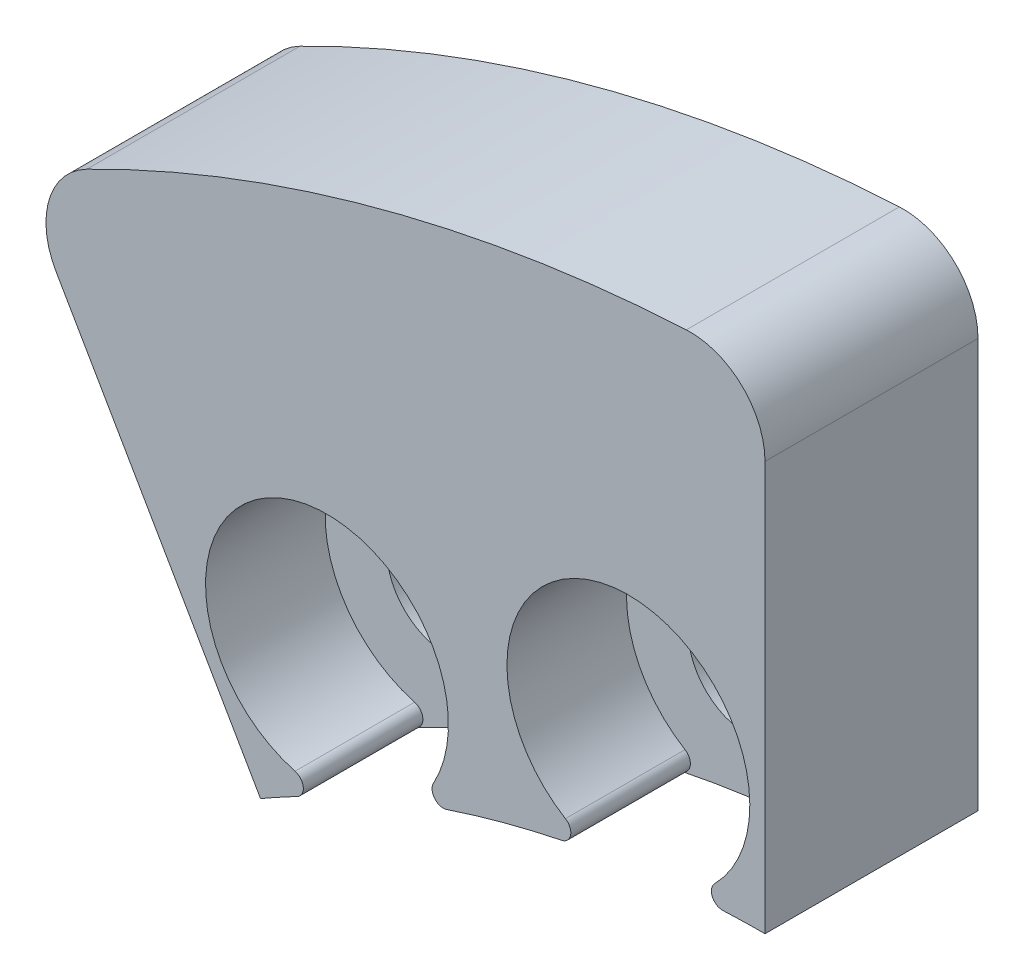
SolidWorks part; units mm, degrees
material "6061 合金"
ref_plane "前视基准面" through (0, 0, 0) normal (0, 0, 1) x (1, 0, 0)
ref_plane "上视基准面" through (0, 0, 0) normal (0, 1, 0) x (1, 0, 0)
ref_plane "右视基准面" through (0, 0, 0) normal (1, 0, 0) x (0, 0, -1)
other "Configuration Table"
sketch "草图1" plane through (0, 0, 0) normal (0, 0, 1) x (1, 0, 0)
  line L0 (0, 0) -> (0, 30)
  line L1 (0, 0) -> (-15, 25.9808)
  circle A0 centre (0, 0) radius 30
  dimension "D1" = 60
  dimension "D2" = 30
extrude "凸台-拉伸2" add sketch "草图1" along normal blind 6 contours L0 A0 L1
sketch "草图2" plane through (0, 0, 6) normal (0, 0, 1) x (1, 0, 0)
  line L0 (-11.7219, 27.6151) -> (-3.6561, 29.7764) construction
  line L1 (-7.689, 28.6958) -> (0, 0) construction
  line L2 (-3.6561, 29.7764) -> (0, 0) construction
  line L3 (0, 0) -> (0, 30) construction
  circle A0 centre (-3.6561, 29.7764) radius 4
  circle A1 centre (-11.7219, 27.6151) radius 4
  arc A2 (0, 30) -> (-15, 25.9808) centre (0, 0) ccw construction
  point P9 (-2.9067, 29.8589)
  dimension "D1" = 8
  dimension "D2" = 8
  dimension "D3" = 15
extrude "凸台-拉伸3" add sketch "草图2" against normal blind 6
sketch "草图4" plane through (0, 0, 6) normal (0, 0, 1) x (1, 0, 0)
  line L0 (0, 0) -> (0, 40)
  line L1 (0, 0) -> (-20, 34.641)
  line L2 (0, 0) -> (-14.0769, 24.3818) construction
  arc A0 (0, 40) -> (-20, 34.641) centre (0, 0) ccw
  dimension "D1" = 80
extrude "凸台-拉伸4" add sketch "草图4" against normal through all
sketch "草图5" plane through (0, 0, 6) normal (0, 0, 1) x (1, 0, 0)
  circle A0 centre (0, 0) radius 27
  dimension "D1" = 54
extrude "切除-拉伸2" cut sketch "草图5" against normal through all
sketch "草图6" plane through (0, 0, 6) normal (0, 0, 1) x (1, 0, 0)
  circle A0 centre (-3.6561, 29.7764) radius 1.6
  circle A1 centre (-11.7219, 27.6151) radius 1.6
  dimension "D1" = 3.2
extrude "切除-拉伸3" cut sketch "草图6" against normal through all
fillet "圆角1" radius 2 2 edges at (0, 40, 3) (-20, 34.641, 3)
fillet "圆角2" [suppressed] radius 2
sketch "草图7" plane through (0, 0, 6) normal (0, 0, 1) x (1, 0, 0)
  circle A0 centre (-11.7219, 27.6151) radius 3.25
  circle A1 centre (-3.6561, 29.7764) radius 3.25
  dimension "D1" = 6.5
extrude "切除-拉伸5" cut sketch "草图7" against normal blind 3.5
fillet "圆角4" radius 0.3 4 edges at (-11.6309, 24.3664, 4.25) (-9.4482, 25.2929, 4.25) (-2.1106, 26.9174, 4.25) (-4.464, 26.6284, 4.25)
sketch "草图8" plane through (0, 0, 6) normal (0, 0, 1) x (1, 0, 0)
  line L0 (-15.6995, 27.1924) -> (-14.0769, 24.3818)
  line L1 (0, 31.3991) -> (0, 28.1537)
  line L6 (0, 27) -> (0, 28.1537)
  line L7 (0, 31.3991) -> (0, 37.9473)
  line L8 (-18.9737, 32.8634) -> (-15.6995, 27.1924)
  line L9 (-14.0769, 24.3818) -> (-13.5, 23.3827)
  arc A14 (-12.5156, 23.924) -> (-13.5, 23.3827) centre (0, 0) ccw
  arc A15 (-12.5156, 23.924) -> (-12.5758, 24.4793) centre (-12.6547, 24.1899) ccw
  arc A16 (-8.873, 26.0511) -> (-12.5758, 24.4793) centre (-11.7219, 27.6151) ccw
  arc A17 (-8.873, 26.0511) -> (-8.5155, 25.622) centre (-8.6101, 25.9067) ccw
  arc A18 (-5.4364, 26.447) -> (-8.5155, 25.622) centre (0, 0) ccw
  arc A19 (-5.4364, 26.447) -> (-5.3413, 26.9974) centre (-5.4968, 26.7409) ccw
  arc A20 (-1.3487, 27.4876) -> (-5.3413, 26.9974) centre (-3.6561, 29.7764) ccw
  arc A21 (-1.3487, 27.4876) -> (-1.1232, 26.9766) centre (-1.1357, 27.2764) ccw
  arc A22 (0, 27) -> (-1.1232, 26.9766) centre (0, 0) ccw
  arc A23 (0, 28.1537) -> (0, 31.3991) centre (-3.6561, 29.7764) ccw
  arc A24 (0, 37.9473) -> (-2.1053, 39.9446) centre (-2, 37.9473) ccw
  arc A25 (-2.1053, 39.9446) -> (-18.1491, 35.6456) centre (0, 0) ccw
  arc A26 (-18.1491, 35.6456) -> (-18.9737, 32.8634) centre (-17.2416, 33.8634) ccw
  arc A27 (-15.6995, 27.1924) -> (-14.0769, 24.3818) centre (-11.7219, 27.6151) ccw
  arc A37 (0, 28.1537) -> (0, 31.3991) centre (-3.6561, 29.7764) ccw
  arc A41 (-15.6995, 27.1924) -> (-14.0769, 24.3818) centre (-11.7219, 27.6151) ccw
  point P0 (0.016, 31.3625)
  point P8 (-15.6739, 26.9974)
  dimension "D1" = 0
extrude "切除-拉伸6" cut sketch "草图8" against normal blind 6
sketch "草图9" plane through (0, 0, 6) normal (0, 0, 1) x (1, 0, 0)
  line L2 (0, 27) -> (0, 37.9473)
  line L3 (-18.9737, 32.8634) -> (-13.5, 23.3827)
  line L4 (0, 27) -> (0, 37.9473)
  line L5 (-18.9737, 32.8634) -> (-13.5, 23.3827)
  arc A12 (0, 27) -> (-1.1232, 26.9766) centre (0, 0) ccw
  arc A13 (0, 37.9473) -> (-2.1053, 39.9446) centre (-2, 37.9473) ccw
  arc A14 (-2.1053, 39.9446) -> (-18.1491, 35.6456) centre (0, 0) ccw
  arc A15 (-18.1491, 35.6456) -> (-18.9737, 32.8634) centre (-17.2416, 33.8634) ccw
  arc A16 (-12.5156, 23.924) -> (-13.5, 23.3827) centre (0, 0) ccw
  arc A17 (-12.5156, 23.924) -> (-12.5758, 24.4793) centre (-12.6547, 24.1899) ccw
  arc A18 (-8.873, 26.0511) -> (-12.5758, 24.4793) centre (-11.7219, 27.6151) ccw
  arc A19 (-8.873, 26.0511) -> (-8.5155, 25.622) centre (-8.6101, 25.9067) ccw
  arc A20 (-5.4364, 26.447) -> (-8.5155, 25.622) centre (0, 0) ccw
  arc A21 (-5.4364, 26.447) -> (-5.3413, 26.9974) centre (-5.4968, 26.7409) ccw
  arc A22 (-1.3487, 27.4876) -> (-5.3413, 26.9974) centre (-3.6561, 29.7764) ccw
  arc A23 (-1.3487, 27.4876) -> (-1.1232, 26.9766) centre (-1.1357, 27.2764) ccw
  arc A24 (0, 27) -> (-1.1232, 26.9766) centre (0, 0) ccw
  arc A25 (0, 37.9473) -> (-2.1053, 39.9446) centre (-2, 37.9473) ccw
  arc A26 (-2.1053, 39.9446) -> (-18.1491, 35.6456) centre (0, 0) ccw
  arc A27 (-18.1491, 35.6456) -> (-18.9737, 32.8634) centre (-17.2416, 33.8634) ccw
  arc A28 (-12.5156, 23.924) -> (-13.5, 23.3827) centre (0, 0) ccw
  arc A29 (-12.5156, 23.924) -> (-12.5758, 24.4793) centre (-12.6547, 24.1899) ccw
  arc A30 (-8.873, 26.0511) -> (-12.5758, 24.4793) centre (-11.7219, 27.6151) ccw
  arc A31 (-8.873, 26.0511) -> (-8.5155, 25.622) centre (-8.6101, 25.9067) ccw
  arc A32 (-5.4364, 26.447) -> (-8.5155, 25.622) centre (0, 0) ccw
  arc A33 (-5.4364, 26.447) -> (-5.3413, 26.9974) centre (-5.4968, 26.7409) ccw
  arc A34 (-1.3487, 27.4876) -> (-5.3413, 26.9974) centre (-3.6561, 29.7764) ccw
  arc A35 (-1.3487, 27.4876) -> (-1.1232, 26.9766) centre (-1.1357, 27.2764) ccw
  dimension "D1" = 0
extrude "切除-拉伸7" cut sketch "草图9" against normal blind 0.3
